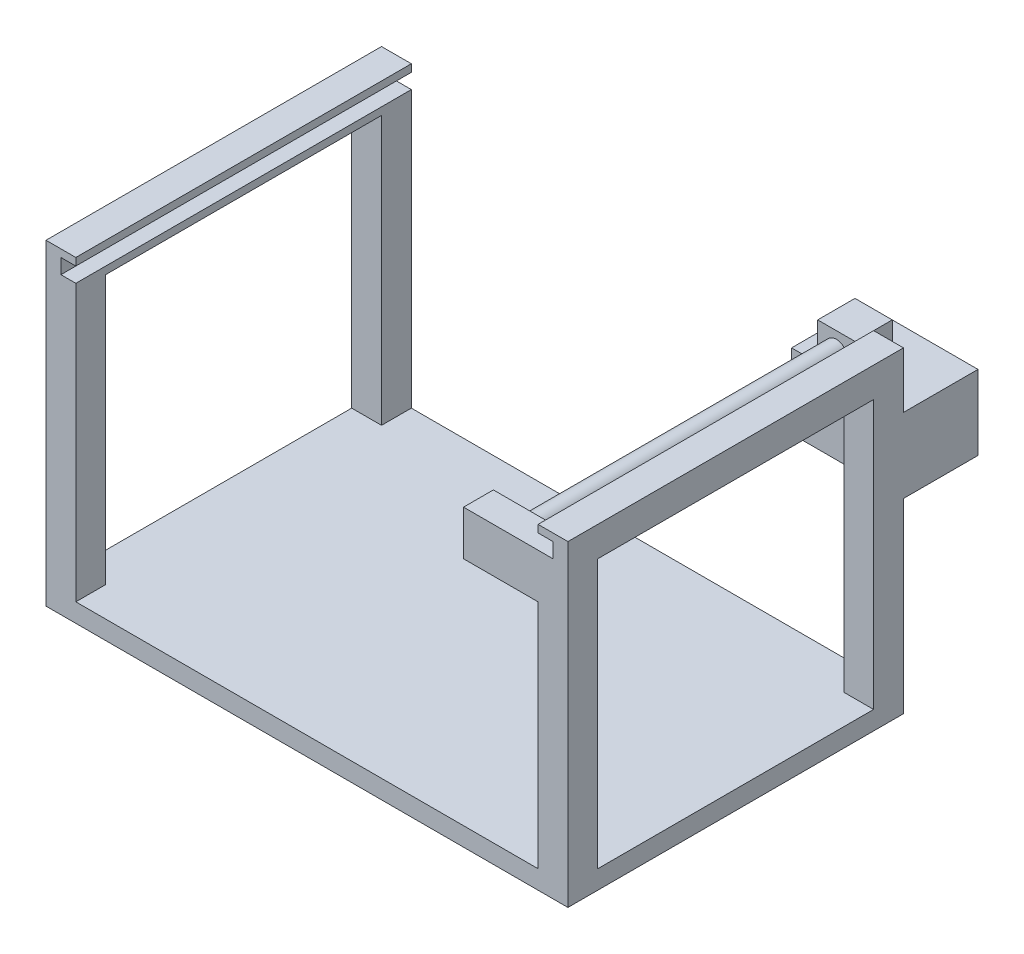
SolidWorks part; units mm, degrees
ref_plane "前视基准面" through (0, 0, 0) normal (0, 0, 1) x (1, 0, 0)
ref_plane "上视基准面" through (0, 0, 0) normal (0, 1, 0) x (1, 0, 0)
ref_plane "右视基准面" through (0, 0, 0) normal (1, 0, 0) x (0, 0, -1)
sketch "草图1" plane through (0, 0, 0) normal (0, 0, 1) x (1, 0, 0)
  line L1 (0, 0) -> (140, 0)
  line L2 (0, 0) -> (0, 5)
  line L3 (0, 5) -> (140, 5)
  line L4 (140, 0) -> (140, 5)
  dimension "D1" = 140
  dimension "D2" = 5
extrude "凸台-拉伸1" add sketch "草图1" against normal blind 90 contours L2 L1 L4 L3
sketch "草图2" plane through (0, 5, 0) normal (0, 1, 0) x (1, 0, 0)
  line L1 (0, 0) -> (8, 0)
  line L2 (0, 0) -> (0, 8)
  line L3 (0, 8) -> (8, 8)
  line L4 (8, 0) -> (8, 8)
  line L5 (0, 90) -> (8, 90)
  line L6 (0, 90) -> (0, 82)
  line L7 (0, 82) -> (8, 82)
  line L8 (8, 90) -> (8, 82)
  line L9 (140, 90) -> (132, 90)
  line L10 (140, 90) -> (140, 82)
  line L11 (140, 82) -> (132, 82)
  line L12 (132, 90) -> (132, 82)
  line L13 (140, 0) -> (132, 0)
  line L14 (140, 0) -> (140, 8)
  line L15 (140, 8) -> (132, 8)
  line L16 (132, 0) -> (132, 8)
  dimension "D1" = 8
  dimension "D2" = 8
  dimension "D3" = 8
  dimension "D4" = 8
  dimension "D5" = 8
  dimension "D6" = 8
  dimension "D7" = 8
  dimension "D8" = 8
extrude "凸台-拉伸2" add sketch "草图2" along normal blind 80
sketch "草图3" plane through (0, 0, -82) normal (0, 0, 1) x (1, 0, 0)
  line L0 (8, 85) -> (8, 5) construction
  line L1 (0, 85) -> (8, 85)
  line L2 (0, 85) -> (0, 77)
  line L3 (0, 77) -> (8, 77)
  line L4 (8, 85) -> (8, 77)
  line L5 (140, 85) -> (140, 5) construction
  line L6 (132, 85) -> (140, 85)
  line L7 (132, 85) -> (132, 77)
  line L8 (132, 77) -> (140, 77)
  line L9 (140, 85) -> (140, 77)
  dimension "D1" = 8
  dimension "D2" = 8
extrude "凸台-拉伸3" add sketch "草图3" along normal up to next
sketch "草图4" plane through (0, 0, 0) normal (0, 0, 1) x (1, 0, 0)
  line L0 (8, 85) -> (8, 5) construction
  line L1 (8, 83) -> (4, 83)
  line L2 (8, 83) -> (8, 79)
  line L3 (8, 79) -> (4, 79)
  line L4 (4, 83) -> (4, 79)
  line L5 (0, 0) -> (0, 85) construction
  line L10 (70, 5) -> (70, 0) construction
  line L13 (0, 77) -> (8, 77) construction
  line L14 (136, 83) -> (136, 79)
  line L15 (132, 79) -> (136, 79)
  line L16 (132, 83) -> (132, 79)
  line L17 (132, 83) -> (136, 83)
  point P15 (70, 2.5)
  dimension "D1" = 4
  dimension "D2" = 2
  dimension "D3" = 4
  dimension "D4" = 70
extrude "切除-拉伸1" cut sketch "草图4" against normal up to surface (90 mm away) up to face at (70, 43.75, -90)
sketch "草图5" plane through (0, 0, -90) normal (0, 0, -1) x (-1, 0, 0)
  line L0 (-140, 0) -> (-140, 85) construction
  line L1 (-140, 70) -> (-110, 70)
  line L2 (-140, 70) -> (-140, 50)
  line L3 (-140, 50) -> (-110, 50)
  line L4 (-110, 70) -> (-110, 50)
  line L5 (0, 0) -> (-140, 0) construction
  dimension "D1" = 30
  dimension "D2" = 20
  dimension "D3" = 50
extrude "凸台-拉伸4" add sketch "草图5" along normal blind 20 contours L2 L1 L4 L3
sketch "草图6" plane through (0, 70, 0) normal (0, 1, 0) x (1, 0, 0)
  line L0 (132, 90) -> (110, 90) construction
  line L1 (117, 100) -> (127, 100)
  line L2 (117, 100) -> (117, 90)
  line L3 (117, 90) -> (127, 90)
  line L4 (127, 100) -> (127, 90)
  line L5 (140, 110) -> (140, 90) construction
  dimension "D1" = 10
  dimension "D2" = 10
  dimension "D3" = 13
extrude "凸台-拉伸5" add sketch "草图6" along normal blind 10 contours L2 L1 L4 L3
sketch "草图7" plane through (0, 0, -90) normal (0, 0, 1) x (1, 0, 0)
  line L0 (117, 75) -> (127, 75) construction
  line L1 (117, 80) -> (117, 70) construction
  line L2 (127, 80) -> (127, 70) construction
  line L3 (117, 80) -> (127, 80) construction
  line L4 (122, 80) -> (122, 69.6949) construction
  circle A0 centre (122, 75) radius 3
  dimension "D1" = 6
extrude "凸台-拉伸6" add sketch "草图7" along normal up to surface (82 mm away) up to face at (136, 41, -8)
sketch "草图8" plane through (132, 0, 0) normal (-1, 0, 0) x (0, 0, 1)
  line L5 (-8, 77) -> (-8, 5) construction
  line L6 (0, 79) -> (-8, 79)
  line L7 (0, 79) -> (0, 67)
  line L8 (0, 67) -> (-8, 67)
  line L9 (-8, 79) -> (-8, 67)
  dimension "D1" = 12
extrude "凸台-拉伸7" add sketch "草图8" along normal blind 20 contours L7 L6 L9 L8
sketch "草图9" plane through (136, 0, 0) normal (-1, 0, 0) x (0, 0, 1)
  line L0 (-90, 79) -> (0, 79) construction
  line L1 (-88.0175, 79) -> (-82.0175, 79)
  line L2 (-88.0175, 79) -> (-88.0175, 82)
  line L3 (-88.0175, 82) -> (-82.0175, 82)
  line L4 (-82.0175, 79) -> (-82.0175, 82)
  dimension "D1" = 6
  dimension "D2" = 3
